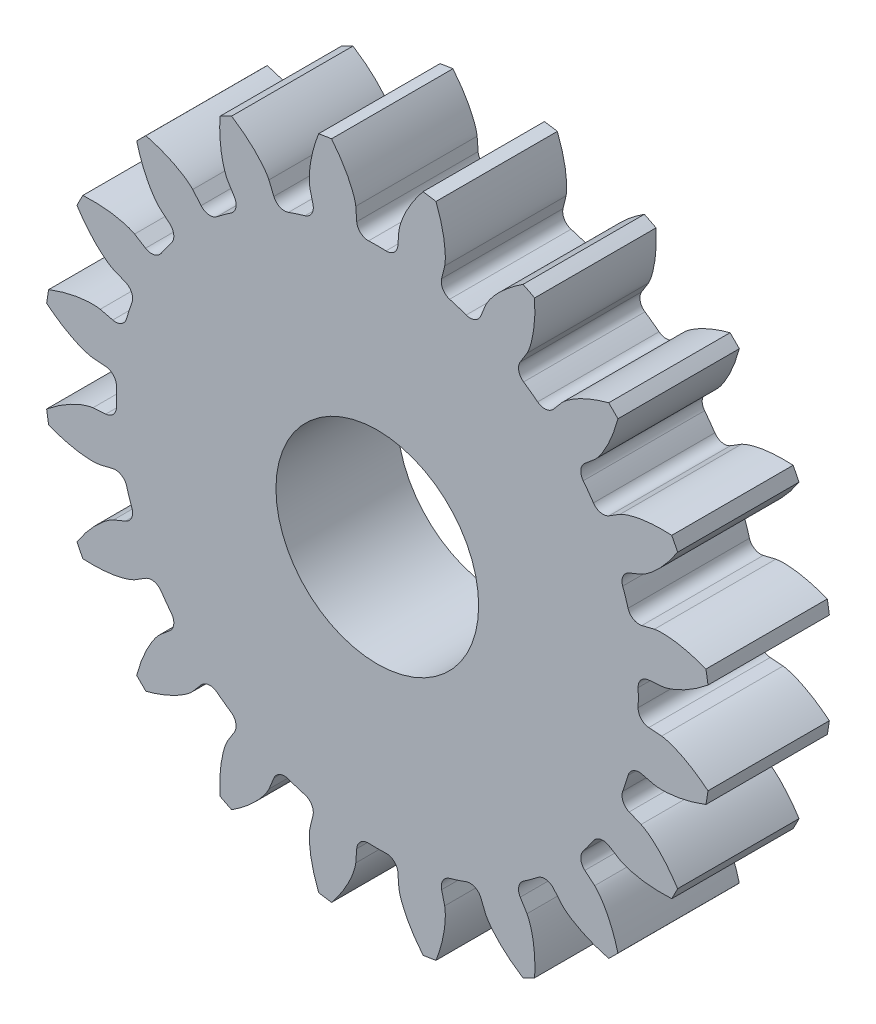
SolidWorks part; units mm, degrees
ref_plane "Front Plane" through (0, 0, 0) normal (0, 0, 1) x (1, 0, 0)
ref_plane "Top Plane" through (0, 0, 0) normal (0, 1, 0) x (1, 0, 0)
ref_plane "Right Plane" through (0, 0, 0) normal (1, 0, 0) x (0, 0, -1)
ref_axis "Gear Axis" through (0, 0, -0.2501) along (0, 0, 1)
sketch "Blank Sketch" plane through (0, 0, 0) normal (0, 0, 1) x (1, 0, 0)
  circle A0 centre (0, 0) radius 13.75
  dimension "OD" = 27.5
extrude "Blank" add sketch "Blank Sketch" along normal blind 5
sketch "Tooth Space Sketch" plane through (0, 0, 0) normal (0, 0, 1) x (1, 0, 0)
  line L0 (11.7126, 0.8876) -> (11.1829, 0.8474)
  line L1 (11.7126, -0.8876) -> (11.1829, -0.8474)
  line L2 (14.705, 2.9601) -> (14.705, -2.9601)
  arc A0 (11.1829, 0.8474) -> (10.744, 0.358) centre (11.2188, 0.3738) ccw
  arc A1 (10.744, -0.358) -> (11.1829, -0.8474) centre (11.2188, -0.3738) ccw
  arc A2 (10.744, -0.358) -> (10.744, 0.358) centre (0, 0) ccw
  spline S0 degree 4 poles (11.7126, 0.8876) (11.718, 0.8881) (11.7333, 0.8898) (11.7621, 0.8941) (11.8087, 0.9028) (11.8679, 0.9161) (11.9438, 0.936) (12.0325, 0.9629) (12.1291, 0.9959) (12.2333, 1.0356) (12.3362, 1.0785) (12.4379, 1.1244) (12.5383, 1.1729) (12.6587, 1.2348) (12.8015, 1.3135) (12.9658, 1.4118) (13.1489, 1.5308) (13.3319, 1.66) (13.5089, 1.7935) (13.6838, 1.9356) (13.8504, 2.0781) (14.0193, 2.2333) (14.173, 2.3803) (14.3404, 2.5526) (14.474, 2.694) (14.6449, 2.8885) (14.7442, 3.0057) (14.8584, 3.1456) (14.9081, 3.2092) (14.9387, 3.2482) knots 0 0 0 0 0 0.005377 0.015084 0.028532 0.04661 0.064855 0.092111 0.119476 0.146842 0.174209 0.201575 0.228941 0.256307 0.307035 0.361767 0.4165 0.471232 0.525964 0.580697 0.635429 0.690161 0.744894 0.799626 0.854358 0.909091 0.954545 1 1 1 1 1 construction
  spline S1 degree 4 poles (11.7126, 0.8876) (11.718, 0.8881) (11.7333, 0.8898) (11.7621, 0.8941) (11.8087, 0.9028) (11.8679, 0.9161) (11.9438, 0.936) (12.0325, 0.9629) (12.1291, 0.9959) (12.2333, 1.0356) (12.3362, 1.0785) (12.4379, 1.1244) (12.5383, 1.1729) (12.6587, 1.2348) (12.8015, 1.3135) (12.9658, 1.4118) (13.1489, 1.5308) (13.3319, 1.66) (13.5089, 1.7935) (13.6838, 1.9356) (13.8504, 2.0781) (14.0193, 2.2333) (14.173, 2.3803) (14.3404, 2.5526) (14.474, 2.694) (14.6078, 2.8463) (14.6723, 2.9214) (14.705, 2.9601) knots 0 0 0 0 0 0.005377 0.015084 0.028532 0.04661 0.064855 0.092111 0.119476 0.146842 0.174209 0.201575 0.228941 0.256307 0.307035 0.361767 0.4165 0.471232 0.525964 0.580697 0.635429 0.690161 0.744894 0.799626 0.854358 0.909091 0.909091 0.909091 0.909091 0.909091
  spline S2 degree 4 poles (11.7126, -0.8876) (11.718, -0.8881) (11.7333, -0.8898) (11.7621, -0.8941) (11.8087, -0.9028) (11.8679, -0.9161) (11.9438, -0.936) (12.0325, -0.9629) (12.1291, -0.9959) (12.2333, -1.0356) (12.3362, -1.0785) (12.4379, -1.1244) (12.5383, -1.1729) (12.6587, -1.2348) (12.8015, -1.3135) (12.9658, -1.4118) (13.1489, -1.5308) (13.3319, -1.66) (13.5089, -1.7935) (13.6838, -1.9356) (13.8504, -2.0781) (14.0193, -2.2333) (14.173, -2.3803) (14.3404, -2.5526) (14.474, -2.694) (14.6449, -2.8885) (14.7442, -3.0057) (14.8584, -3.1456) (14.9081, -3.2092) (14.9387, -3.2482) knots 0 0 0 0 0 0.005377 0.015084 0.028532 0.04661 0.064855 0.092111 0.119476 0.146842 0.174209 0.201575 0.228941 0.256307 0.307035 0.361767 0.4165 0.471232 0.525964 0.580697 0.635429 0.690161 0.744894 0.799626 0.854358 0.909091 0.954545 1 1 1 1 1 construction
  spline S3 degree 4 poles (11.7126, -0.8876) (11.718, -0.8881) (11.7333, -0.8898) (11.7621, -0.8941) (11.8087, -0.9028) (11.8679, -0.9161) (11.9438, -0.936) (12.0325, -0.9629) (12.1291, -0.9959) (12.2333, -1.0356) (12.3362, -1.0785) (12.4379, -1.1244) (12.5383, -1.1729) (12.6587, -1.2348) (12.8015, -1.3135) (12.9658, -1.4118) (13.1489, -1.5308) (13.3319, -1.66) (13.5089, -1.7935) (13.6838, -1.9356) (13.8504, -2.0781) (14.0193, -2.2333) (14.173, -2.3803) (14.3404, -2.5526) (14.474, -2.694) (14.6078, -2.8463) (14.6723, -2.9214) (14.705, -2.9601) knots 0 0 0 0 0 0.005377 0.015084 0.028532 0.04661 0.064855 0.092111 0.119476 0.146842 0.174209 0.201575 0.228941 0.256307 0.307035 0.361767 0.4165 0.471232 0.525964 0.580697 0.635429 0.690161 0.744894 0.799626 0.854358 0.909091 0.909091 0.909091 0.909091 0.909091
  dimension "Root" = 10.75
  dimension "Fillet" = 0.475
extrude "Tooth Space" cut sketch "Tooth Space Sketch" against normal through all both and the other way through all both
pattern_circular "Teeth" count 20 over 360 about axis through (0, 0, -0.2501) along (0, 0, 1) of "Tooth Space"
sketch "Bore Sketch" plane through (0, 0, 0) normal (0, 0, 1) x (1, 0, 0)
  circle A0 centre (0, 0) radius 4.175
  dimension "Bore" = 8.35
extrude "Bore" cut sketch "Bore Sketch" against normal through all both and the other way through all both
equation "\"No. of Teeth\"= 20"
equation "\"Module\"= 1.25"
equation "\"Bore Diameter\"= 8.35"
equation "\"Pressure Angle\"= 20"
equation "\"Outer Diameter\"= ( \"No. of Teeth\" + 2 ) * \"Module\""
equation "\"Pitch Diameter\"= \"No. of Teeth\" * \"Module\""
equation "\"Backlash\"= IIF ( \"Module\" <= 1 , 0.3 * \"Module\" , 0.3 )"
equation "\"Arc Length\"= ( ( \"Module\" * pi ) / 2 + \"Backlash\" )"
equation "\"Fillet Radius\"= 0.38 * \"Module\""
equation "\"Tooth Depth\"= IIF ( \"Module\" <= 1.25 , \"Module\" * 2.4 , \"Module\" * 2.25 )"
equation "\"Face Width\"= 5"
equation "\"Root Diameter\"= \"Outer Diameter\" - 2 * \"Tooth Depth\""
equation "\"Base Diameter\"= \"Pitch Diameter\" * cos ( \"Pressure Angle\" )"
equation "\"Base Radius\"= \"Base Diameter\" / 2"
equation "\"Tooth Thickness\"= \"Module\" * pi - \"Arc Length\""
equation "\"Half Space Angle\"= ( \"Arc Length\" / \"Pitch Diameter\" ) * 180 / pi"
equation "\"Involute Fn\"= tan ( \"Pressure Angle\" ) - \"Pressure Angle\" * pi / 180"
equation "\"Flank Offset\"= \"Arc Length\" / \"Pitch Diameter\" - \"Involute Fn\""
equation "\"Tip Cap Diameter\"= \"Outer Diameter\" + 2 * \"Module\""
equation "\"Flank Start Diameter\"= IIF ( \"Base Diameter\" >= ( \"Root Diameter\" + 3 * \"Fillet Radius\" ) , \"Base Diameter\" , \"Root Diameter\" + 3 * \"Fillet Radius\" )"
equation "\"Involute t1\"= ( abs ( ( \"Flank Start Diameter\" / \"Base Diameter\" ) ^ 2 - 1 ) ) ^ 0.5"
equation "\"Involute t2\"= ( abs ( ( \"Tip Cap Diameter\" / \"Base Diameter\" ) ^ 2 - 1 ) ) ^ 0.5"
equation "\"Flank Arc Radius\"= ( \"Pitch Diameter\" / 2 ) * sin ( \"Pressure Angle\" )"
equation "\"Flank Centre Angle\"= \"Half Space Angle\" + \"Pressure Angle\""
equation "\"OD@Blank Sketch\"= \"Outer Diameter\""
equation "\"Width@Blank\"= \"Face Width\""
equation "\"Root@Tooth Space Sketch\"= \"Root Diameter\" / 2"
equation "\"Fillet@Tooth Space Sketch\"= \"Fillet Radius\""
equation "\"Count@Teeth\"= \"No. of Teeth\""
equation "\"Bore@Bore Sketch\"= \"Bore Diameter\""
